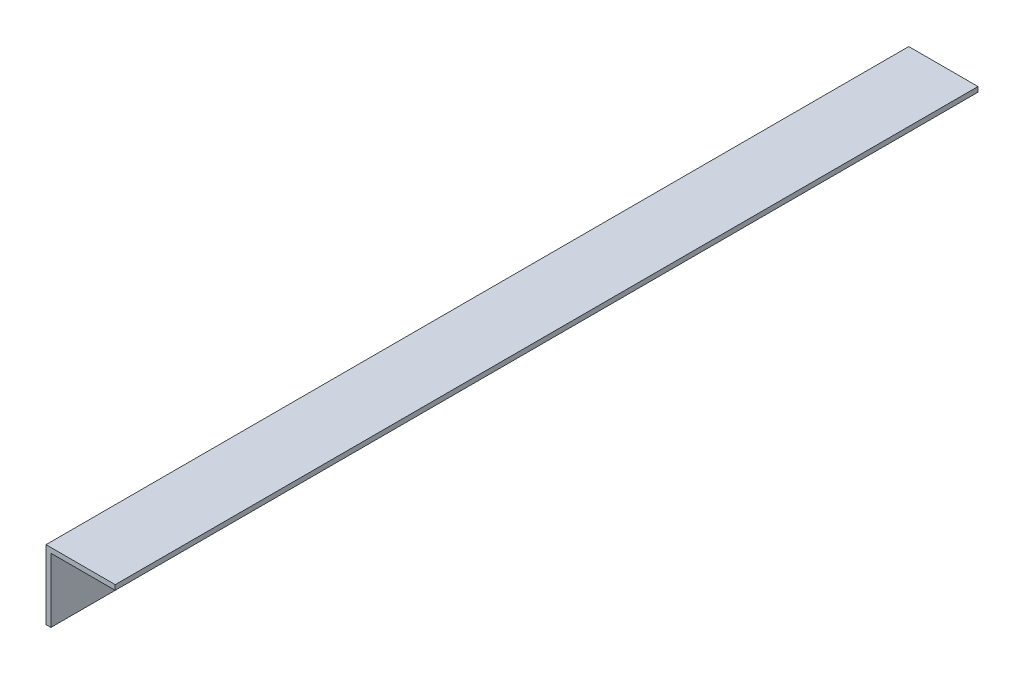
SolidWorks part; units mm, degrees
ref_plane "Alzado" through (0, 0, 0) normal (0, 0, 1) x (1, 0, 0)
ref_plane "Planta" through (0, 0, 0) normal (0, 1, 0) x (1, 0, 0)
ref_plane "Vista lateral" through (0, 0, 0) normal (1, 0, 0) x (0, 0, -1)
sketch "Croquis1" plane through (0, 0, 0) normal (0, 0, 1) x (1, 0, 0)
  line L0 (0, 0) -> (88.9, 0)
  line L1 (0, 0) -> (0, -88.9)
  line L2 (6.35, -6.35) -> (6.35, -88.9)
  line L3 (6.35, -6.35) -> (88.9, -6.35)
  line L4 (88.9, -6.35) -> (88.9, 0)
  line L5 (6.35, -88.9) -> (0, -88.9)
  dimension "D1" = 88.9
  dimension "D2" = 88.9
  dimension "D3" = 6.35
extrude "Saliente-Extruir1" add sketch "Croquis1" along normal blind 1107.6
